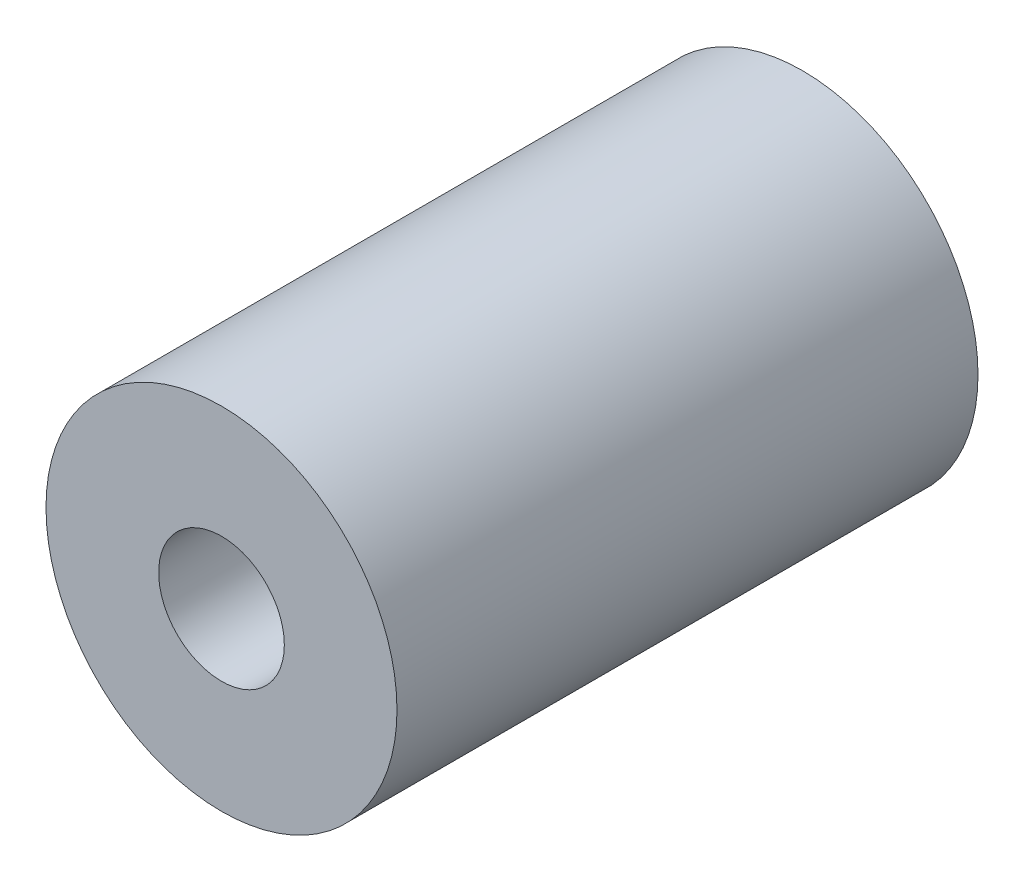
SolidWorks part; units mm, degrees
ref_plane "前视基准面" through (0, 0, 0) normal (0, 0, 1) x (1, 0, 0)
ref_plane "上视基准面" through (0, 0, 0) normal (0, 1, 0) x (1, 0, 0)
ref_plane "右视基准面" through (0, 0, 0) normal (1, 0, 0) x (0, 0, -1)
other "Configuration Table"
sketch "草图1" plane through (0, 0, 0) normal (0, 0, 1) x (1, 0, 0)
  circle A0 centre (0, 0) radius 4.9
  circle A1 centre (0, 0) radius 2.65
  dimension "D1" = 9.8
  dimension "D2" = 5.3
extrude "凸台-拉伸1" add sketch "草图1" along normal blind 24.5
sketch "草图2" [suppressed] plane through (0, 0, 10) normal (0, 0, 1) x (1, 0, 0)
  circle A0 centre (0, 0) radius 7.4
  circle A1 centre (0, 0) radius 2.65 construction
  circle A2 centre (0, 0) radius 2.65
  dimension "D1" = 14.8
extrude "凸台-拉伸2" [suppressed] add sketch "草图2" against normal blind 10
sketch "草图3" plane through (0, 0, 0) normal (0, 0, -1) x (-1, 0, 0)
  circle A0 centre (0, 0) radius 7.4
  circle A1 centre (0, 0) radius 2.65 construction
  circle A2 centre (0, 0) radius 2.65
  dimension "D1" = 14.8
extrude "凸台-拉伸3" add sketch "草图3" against normal blind 24.5
